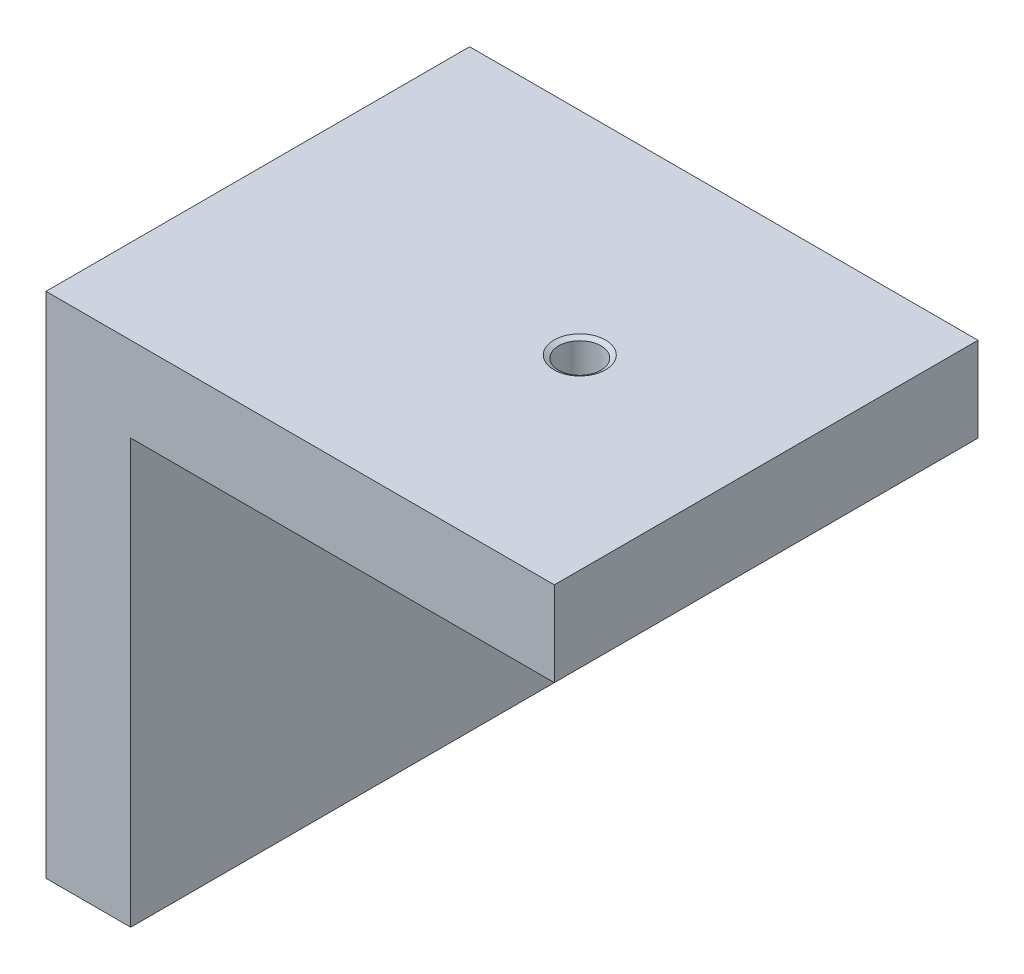
SolidWorks part; units mm, degrees
ref_plane "Piano frontale" through (0, 0, 0) normal (0, 0, 1) x (1, 0, 0)
ref_plane "Piano superiore" through (0, 0, 0) normal (0, 1, 0) x (1, 0, 0)
ref_plane "Piano destro" through (0, 0, 0) normal (1, 0, 0) x (0, 0, -1)
sketch "Schizzo1" plane through (0, 0, 0) normal (0, 0, 1) x (1, 0, 0)
  line L0 (0, 0) -> (0, 30)
  line L1 (0, 30) -> (30, 30)
  line L2 (30, 30) -> (30, 25)
  line L3 (30, 25) -> (5, 25)
  line L4 (5, 25) -> (5, 0)
  line L5 (5, 0) -> (0, 0)
  dimension "D1" = 30
  dimension "D2" = 5
  dimension "D3" = 30
  dimension "D4" = 5
extrude "Estrusione-Estrusione1" add sketch "Schizzo1" along normal blind 25
sketch "Schizzo2" plane through (0, 0, 0) normal (-1, 0, 0) x (0, 0, 1)
  line L0 (12.5, 0) -> (12.5, 16.7234) construction
  line L1 (25, 0) -> (0, 0) construction
  circle A0 centre (12.5, 18) radius 3.5
  dimension "D1" = 7
  dimension "D2" = 18
extrude "Taglio-Estrusione1" cut sketch "Schizzo2" against normal blind 25
sketch "Schizzo3" plane through (0, 30, 0) normal (0, 1, 0) x (1, 0, 0)
  line L0 (0, -12.5) -> (30, -12.5) construction
  line L1 (0, -25) -> (0, 0) construction
  line L2 (30, -25) -> (30, 0) construction
  point P6 (19, -12.5)
  dimension "D1" = 19
hole_wizard "Foro filettato M3-1" positions "Schizzo5" profile "Schizzo4" tap size "M3" standard "ISO"
sketch "Schizzo5" plane through (0, 30, 0) normal (0, 1, 0) x (1, 0, 0)
  point P0 (19, -12.5)
sketch "Schizzo4" plane through (19, 30, 12.5) normal (1, 0, 0) x (0, 0, 1)
  line L0 (0, 0) -> (0, 9.2511)
  line L1 (0, 9.2511) -> (1.25, 8.5)
  line L2 (1.25, 8.5) -> (1.25, 0.1588)
  line L3 (1.25, 0.1588) -> (1.525, 0)
  line L5 (1.525, 0) -> (0, 0)
  line L6 (-1.25, 0.1588) -> (-1.525, 0) construction
  line L10 (0, 9.2511) -> (-1.25, 8.5) construction
  line L11 (0, -6.35) -> (0, 107.95) construction
  dimension "Tap Drill Dia." = 2.5
  dimension "Tap Drill Depth" = 8.5
  dimension "Near C'Sink Dia." = 3.05
  dimension "Near C'Sink Angle" = 120
  dimension "Drill Angle" = 118
cosmetic thread "Filettatura del foro1" parameters "D1"=5, "D2"=3
